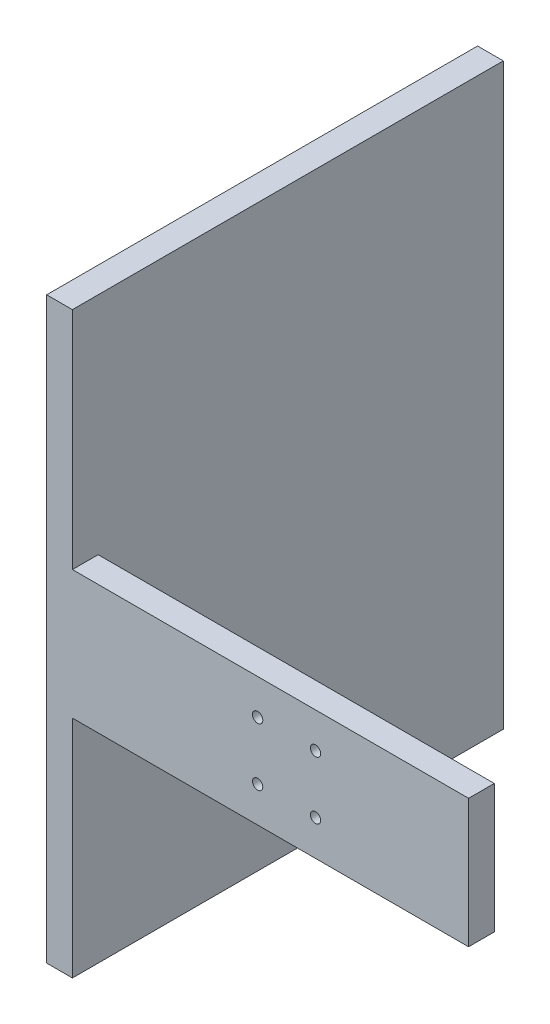
SolidWorks part; units mm, degrees
material "ABS"
ref_plane "Front Plane" through (0, 0, 0) normal (0, 0, 1) x (1, 0, 0)
ref_plane "Top Plane" through (0, 0, 0) normal (0, 1, 0) x (1, 0, 0)
ref_plane "Right Plane" through (0, 0, 0) normal (1, 0, 0) x (0, 0, -1)
ref_plane "P_plate_on_t" through (0, 0, 28) normal (0, 0, 1) x (1, 0, 0)
sketch "Sketch1" plane through (0, 0, 28) normal (0, 0, 1) x (1, 0, 0)
  line L1 (-151.1, -10) -> (-85.5, -10)
  line L2 (-151.1, -10) -> (-151.1, 10)
  line L3 (-151.1, 10) -> (-85.5, 10)
  line L4 (-85.5, -10) -> (-85.5, 10)
extrude "Boss-Extrude1" add sketch "Sketch1" along normal blind 4
ref_plane "P_torso_shel" through (-151.1, 0, 0) normal (1, 0, 0) x (0, 0, -1)
sketch "Sketch2" plane through (-151.1, 0, 0) normal (1, 0, 0) x (0, 0, -1)
  line L1 (-32, -45) -> (35, -45)
  line L2 (-32, -45) -> (-32, 45)
  line L3 (-32, 45) -> (35, 45)
  line L4 (35, -45) -> (35, 45)
extrude "Boss-Extrude2" add sketch "Sketch2" along normal blind 4
ref_plane "P_web" through (0, 0, 28) normal (0, 0, 1) x (1, 0, 0)
sketch "Sketch3" plane through (0, 0, 28) normal (0, 0, 1) x (1, 0, 0)
  circle A0 centre (-109.3, 4.5) radius 0.8
  circle A1 centre (-109.3, -4.5) radius 0.8
  circle A2 centre (-118.3, 4.5) radius 0.8
  circle A3 centre (-118.3, -4.5) radius 0.8
extrude "Cut-Extrude2" cut sketch "Sketch3" along normal blind 4
ref_plane "P_shelf_top" through (-151.1, 0, 0) normal (1, 0, 0) x (0, 0, -1)
sketch "Sketch4" plane through (-151.1, 0, 0) normal (1, 0, 0) x (0, 0, -1)
  circle A0 centre (15, -30) radius 0.8
  circle A1 centre (-15, -30) radius 0.8
  circle A2 centre (15, 30) radius 0.8
  circle A3 centre (-15, 30) radius 0.8
extrude "Cut-Extrude4" cut sketch "Sketch4" along normal blind 3.5
